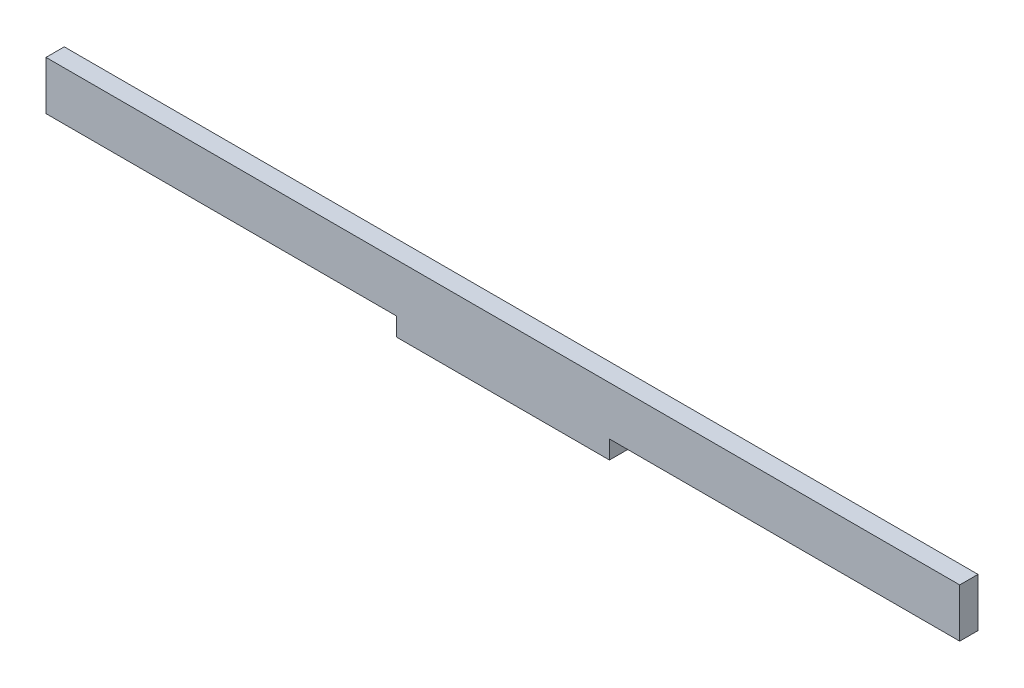
SolidWorks part; units mm, degrees
ref_plane "Спереди" through (0, 0, 0) normal (0, 0, 1) x (1, 0, 0)
ref_plane "Сверху" through (0, 0, 0) normal (0, 1, 0) x (1, 0, 0)
ref_plane "Справа" through (0, 0, 0) normal (1, 0, 0) x (0, 0, -1)
sketch "Эскиз1" plane through (0, 0, 0) normal (0, 0, 1) x (1, 0, 0)
  line L0 (-30.5787, -5.3082) -> (26.9213, -5.3082)
  line L1 (-123.0787, 2.6918) -> (26.9213, 2.6918)
  line L2 (-123.0787, 2.6918) -> (-123.0787, -5.3082)
  line L3 (-123.0787, -5.3082) -> (-65.5787, -5.3082)
  line L4 (26.9213, 2.6918) -> (26.9213, -5.3082)
  line L6 (-65.5787, -5.3082) -> (-65.5787, -8.3082)
  line L7 (-65.5787, -8.3082) -> (-30.5787, -8.3082)
  line L8 (-30.5787, -5.3082) -> (-30.5787, -8.3082)
  dimension "D1" = 35
  dimension "D2" = 3
  dimension "D3" = 57.5
  dimension "D4" = 150
  dimension "D5" = 8
extrude "Бобышка-Вытянуть1" add sketch "Эскиз1" along normal blind 3
